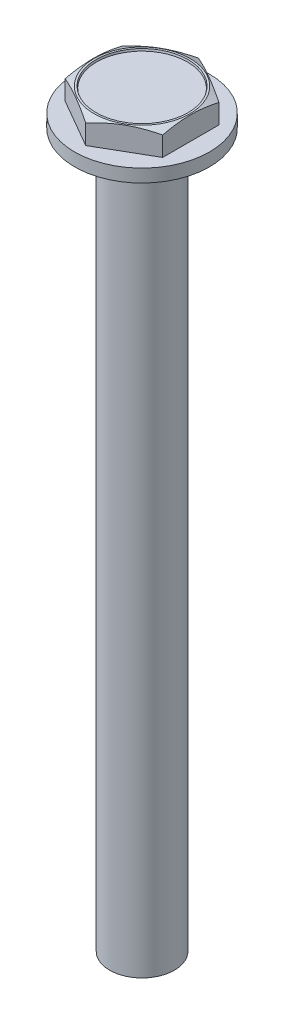
SolidWorks part; units mm, degrees
ref_plane "Plane1" through (0, 0, 0) normal (0, 0, 1) x (1, 0, 0)
ref_plane "Plane2" through (0, 0, 0) normal (0, 1, 0) x (1, 0, 0)
ref_plane "Plane3" through (0, 0, 0) normal (1, 0, 0) x (0, 0, -1)
sketch "Sketch1" plane through (0, 0, 0) normal (0, 0, 1) x (1, 0, 0)
  line L0 (0, 0) -> (3.302, 0)
  line L1 (3.302, 0) -> (3.302, 1.3325)
  line L2 (3.302, 1.3325) -> (2.3466, 1.778)
  line L3 (2.3466, 1.778) -> (2.2527, 1.778)
  line L4 (2.2527, 1.778) -> (2.2292, 1.6841)
  line L5 (2.2292, 1.6841) -> (0, 1.6841)
  line L6 (0, 1.6841) -> (0, 0)
  line L7 (0, 0) -> (0, 100) construction
revolve "Base-Revolve" add sketch "Sketch1" angle 360 about L7
sketch "Sketch2" plane through (0, 0, 0) normal (0, 0, 1) x (1, 0, 0)
  line L0 (0, 0) -> (0, 100) construction
  line L1 (0, -34.925) -> (1.5875, -34.925)
  line L2 (1.5875, -34.925) -> (1.5875, 0)
  line L3 (1.5875, 0) -> (0, 0)
  line L4 (0, 0) -> (0, -34.925)
  dimension "D1" = 34.925
revolve "Boss-Revolve1" add sketch "Sketch2" angle 360 about L0
ref_plane "Plane4" through (0, 1.778, 0) normal (0, 1, 0) x (-1, 0, 0)
sketch "Sketch3" plane through (0, 1.778, 0) normal (0, 1, 0) x (-1, 0, 0)
  line L0 (2.3876, 1.3785) -> (0, 2.757)
  line L1 (0, 2.757) -> (-2.3876, 1.3785)
  line L2 (-2.3876, 1.3785) -> (-2.3876, -1.3785)
  line L3 (-2.3876, -1.3785) -> (0, -2.757)
  line L4 (0, -2.757) -> (2.3876, -1.3785)
  line L5 (2.3876, -1.3785) -> (2.3876, 1.3785)
  line L6 (3.6322, 3.6322) -> (-3.6322, 3.6322)
  line L7 (-3.6322, 3.6322) -> (-3.6322, -3.6322)
  line L8 (-3.6322, -3.6322) -> (3.6322, -3.6322)
  line L9 (3.6322, -3.6322) -> (3.6322, 3.6322)
extrude "Cut-Extrude1" cut sketch "Sketch3" against normal blind 1.143
